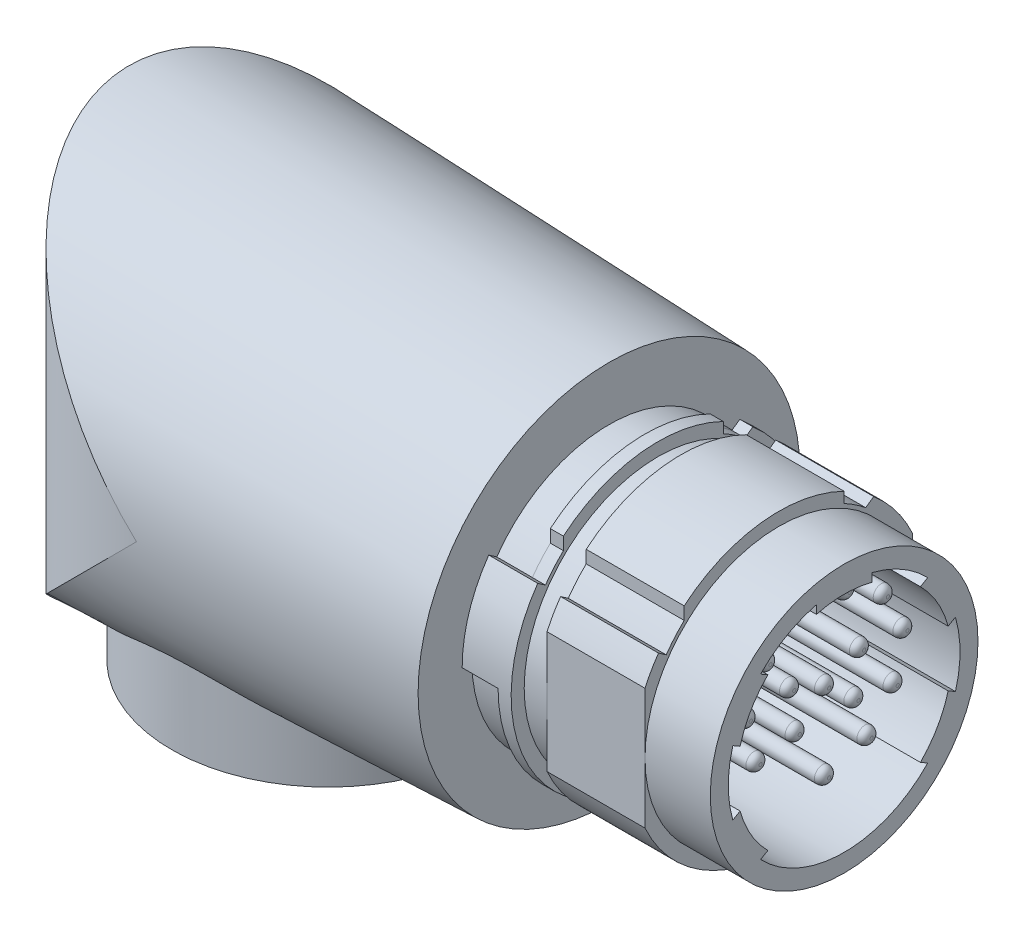
SolidWorks part; units mm, degrees
material "ABS"
ref_plane "Front Plane" through (0, 0, 0) normal (0, 0, 1) x (1, 0, 0)
ref_plane "Top Plane" through (0, 0, 0) normal (0, 1, 0) x (1, 0, 0)
ref_plane "Right Plane" through (0, 0, 0) normal (1, 0, 0) x (0, 0, -1)
sketch "Sketch3" plane through (0, 0, 0) normal (0, 0, 1) x (1, 0, 0)
  line L0 (-15.494, 16.0655) -> (40.132, 16.0655) construction
  line L4 (-15.494, 16.0655) -> (-15.494, 32.258)
  line L5 (-15.494, 32.258) -> (21.844, 30.9245)
  line L6 (21.844, 30.9245) -> (21.844, 28.7655)
  line L7 (21.844, 28.7655) -> (40.132, 28.7655)
  line L8 (40.132, 28.7655) -> (40.132, 16.0655)
  line L9 (40.132, 16.0655) -> (-15.494, 16.0655)
  line L11 (55, 0) -> (-55, 0) construction
  line L12 (0, -55) -> (0, 55) construction
  dimension "D1" = 16.0655
  dimension "D2" = 32.385
  dimension "D3" = 29.718
  dimension "D4" = 25.4
  dimension "D5" = 15.494
  dimension "D6" = 18.288
  dimension "D7" = 55.626
revolve "Revolve1" add sketch "Sketch3" angle 360 about L0
sketch "Sketch4" plane through (0, 0, 0) normal (0, 1, 0) x (1, 0, 0)
  line L0 (21.844, 14.859) -> (-15.494, 16.1925) construction
  line L2 (-15.494, 16.1925) -> (-15.494, -16.1925) construction
  line L3 (-15.494, -16.1925) -> (21.844, -14.859) construction
  line L5 (0.6882, 15.6146) -> (0.6882, 19.05)
  line L6 (0.6882, 19.05) -> (-24.7118, 19.05)
  line L7 (-24.7118, 19.05) -> (-24.7118, -19.05)
  line L8 (-24.7118, -19.05) -> (0.6882, -19.05)
  line L9 (0.6882, -19.05) -> (0.6882, -15.6146)
  line L10 (21.844, 14.859) -> (-15.494, 16.1925) construction
  line L12 (-15.494, -16.1925) -> (21.844, -14.859) construction
  line L14 (0.1305, 0) -> (-15.494, 0) construction
  arc A0 (0.6882, 15.6146) -> (0.6882, -15.6146) centre (0.1305, 0) ccw
  dimension "D1" = 38.1
  dimension "D2" = 25.4
extrude "Extrude3" cut sketch "Sketch4" along normal mid plane 84.582
sketch "Sketch2" plane through (0, 0, 0) normal (0, 1, 0) x (1, 0, 0)
  circle A0 centre (0, 0) radius 12.192
  dimension "D1" = 24.384
extrude "Extrude2" add sketch "Sketch2" along normal blind 7.62
sketch "Sketch5" plane through (0, 0, 0) normal (0, 0, 1) x (1, 0, 0)
  line L0 (21.844, 26.7335) -> (24.638, 26.7335)
  line L1 (21.844, 1.2065) -> (21.844, 30.9245) construction
  line L2 (24.638, 26.7335) -> (24.638, 27.4955)
  line L3 (24.638, 27.4955) -> (25.654, 27.4955)
  line L4 (27.432, 26.4795) -> (27.432, 27.4955)
  line L5 (27.432, 27.4955) -> (35.052, 27.4955)
  line L6 (35.052, 27.4955) -> (35.052, 26.4795)
  line L7 (35.052, 26.4795) -> (40.132, 26.4795)
  line L8 (40.132, 3.3655) -> (40.132, 28.7655) construction
  line L9 (40.132, 26.4795) -> (40.132, 28.7655)
  line L10 (40.132, 28.7655) -> (21.844, 28.7655)
  line L11 (21.844, 28.7655) -> (21.844, 26.7335)
  line L12 (0.6882, 16.0655) -> (40.132, 16.0655) construction
  line L13 (40.132, 16.0655) -> (21.844, 16.0655) construction
  line L14 (-12.1806, 16.0655) -> (21.844, 16.0655) construction
  line L15 (25.654, 27.4955) -> (25.654, 26.4795)
  line L16 (25.654, 26.4795) -> (27.432, 26.4795)
  dimension "D1" = 20.828
  dimension "D2" = 22.86
  dimension "D3" = 20.828
  dimension "D4" = 22.86
  dimension "D5" = 21.336
  dimension "D6" = 5.08
  dimension "D7" = 12.7
  dimension "D8" = 1.778
  dimension "D9" = 15.494
revolve "Cut-Revolve1" cut sketch "Sketch5" angle 360 about L12
sketch "Sketch6" plane through (40.132, 0, 0) normal (1, 0, 0) x (0, 0, -1)
  line L0 (-7.366, 24.8055) -> (-7.366, 23.8226)
  line L1 (-8.7626, 22.2012) -> (-9.3629, 22.6215)
  line L2 (0, 17.8117) -> (0, -17.8117) construction
  line L3 (6.7564, 24.359) -> (7.3787, 24.7947)
  line L4 (5.08, 26.3046) -> (5.08, 25.4795)
  line L5 (0.254, 5.3713) -> (0.254, 4.6383)
  line L6 (3.8593, 6.0887) -> (4.572, 5.5897)
  circle A0 centre (0, 16.0655) radius 11.43 construction
  arc A1 (4.572, 5.5897) -> (0.254, 4.6383) centre (0, 16.0655) cw
  arc A2 (-7.366, 23.8226) -> (-8.7626, 22.2012) centre (0, 16.0655) ccw
  arc A3 (6.7564, 24.359) -> (5.08, 25.4795) centre (0, 16.0655) ccw
  arc A4 (7.3787, 24.7947) -> (5.08, 26.3046) centre (0, 16.0655) ccw
  arc A5 (-7.366, 24.8055) -> (-9.3629, 22.6215) centre (0, 16.0655) ccw
  arc A6 (3.8593, 6.0887) -> (0.254, 5.3713) centre (0, 16.0655) cw
  dimension "D1" = 10.6972
  dimension "D6" = 55
  dimension "D2" = 55
  dimension "D3" = 7.366
  dimension "D4" = 5.08
  dimension "D5" = 1.6764
  dimension "D7" = 0.254
  dimension "D8" = 4.572
  dimension "D9" = 55
extrude "Extrude4" cut sketch "Sketch6" against normal up to surface (18.288 mm away)
sketch "Sketch7" plane through (40.132, 0, 0) normal (1, 0, 0) x (0, 0, -1)
  circle A0 centre (0, 16.0655) radius 9.017
  dimension "D1" = 18.034
extrude "Extrude5" cut sketch "Sketch7" against normal blind 13.97
sketch "Sketch8" plane through (21.844, 0, 0) normal (1, 0, 0) x (0, 0, -1)
  line L0 (-9.3629, 22.6215) -> (-8.7626, 22.2012) construction
  line L1 (-9.3629, 22.6215) -> (-8.7626, 22.2012)
  line L2 (4.572, 5.5897) -> (3.8593, 6.0887) construction
  line L3 (4.572, 5.5897) -> (3.8305, 6.1089)
  line L4 (-8.7626, 22.2012) -> (-8.7387, 22.1844)
  line L5 (-10.668, 16.0655) -> (-11.43, 16.0655)
  line L6 (8.7387, 9.9466) -> (9.3629, 9.5095)
  arc A0 (4.572, 5.5897) -> (7.3787, 24.7947) centre (0, 16.0655) ccw construction
  arc A1 (4.572, 5.5897) -> (9.3629, 9.5095) centre (0, 16.0655) ccw
  circle A2 centre (0, 16.0655) radius 10.668 construction
  arc A3 (-8.7387, 22.1844) -> (-10.668, 16.0655) centre (0, 16.0655) ccw
  arc A4 (-9.3629, 22.6215) -> (0.254, 4.6383) centre (0, 16.0655) ccw construction
  arc A5 (-9.3629, 22.6215) -> (-11.43, 16.0655) centre (0, 16.0655) ccw
  arc A6 (3.8305, 6.1089) -> (8.7387, 9.9466) centre (0, 16.0655) ccw
extrude "Extrude6" add sketch "Sketch8" along normal up to surface (2.794 mm away) up to face at (24.638, 17.8433, 0.0017)
sketch "Sketch9" plane through (40.132, 0, 0) normal (1, 0, 0) x (0, 0, -1)
  line L0 (-9.017, 16.0655) -> (9.017, 16.0655) construction
  line L1 (-15.494, 22.4155) -> (-10.414, 22.4155)
  line L2 (-15.494, 22.4155) -> (-15.494, 9.7155)
  line L3 (-15.494, 9.7155) -> (-10.414, 9.7155)
  line L4 (-10.414, 22.4155) -> (-10.414, 9.7155)
  line L5 (15.494, 22.4155) -> (10.414, 22.4155)
  line L6 (15.494, 22.4155) -> (15.494, 9.7155)
  line L7 (15.494, 9.7155) -> (10.414, 9.7155)
  line L8 (10.414, 22.4155) -> (10.414, 9.7155)
  circle A0 centre (0, 16.0655) radius 10.414 construction
  circle A1 centre (0, 16.0655) radius 9.017 construction
  circle A2 centre (0, 16.0655) radius 9.017 construction
  dimension "D1" = 12.7
  dimension "D2" = 5.08
extrude "Extrude7" cut sketch "Sketch9" against normal up to surface (12.7 mm away) up to face at (27.432, 17.8433, 0.0017)
sketch "Sketch10" plane through (40.132, 0, 0) normal (1, 0, 0) x (0, 0, -1)
  line L0 (-2.159, 24.8202) -> (-2.159, 24.1647)
  line L1 (2.159, 24.1647) -> (2.159, 24.8202)
  line L2 (0, 32.258) -> (0, 16.0655) construction
  line L3 (0, 17.8117) -> (0, -17.8117) construction
  circle A0 centre (0, 16.0655) radius 9.017 construction
  arc A1 (2.159, 24.8202) -> (-2.159, 24.8202) centre (0, 16.0655) ccw
  arc A2 (2.159, 24.1647) -> (-2.159, 24.1647) centre (0, 16.0655) ccw
  spline S0 degree 3 poles (-15.6146, 16.0655) (-15.6186, 16.1773) (-15.6214, 16.2919) (-15.6246, 16.5181) (-15.6256, 16.8571) (-15.6157, 17.1949) (-15.5813, 17.8692) (-15.5391, 18.3167) (-15.3547, 19.6532) (-15.1551, 20.5364) (-14.7333, 21.8486) (-14.5721, 22.2839) (-14.2058, 23.15) (-14.0001, 23.5816) (-13.3217, 24.8493) (-12.7865, 25.6647) (-11.8407, 26.8366) (-11.5015, 27.2186) (-10.769, 27.9633) (-10.3761, 28.3251) (-9.132, 29.3552) (-8.2104, 29.977) (-6.6493, 30.7837) (-6.1065, 31.0271) (-4.9828, 31.4539) (-4.4004, 31.6381) (-3.4923, 31.8657) (-3.1824, 31.9335) (-2.5608, 32.0498) (-2.2486, 32.0985) (-1.3078, 32.216) (-0.6751, 32.2565) (0.6017, 32.2595) (1.2515, 32.2208) (2.5144, 32.0673) (3.1321, 31.9533) (4.3416, 31.6552) (4.9365, 31.4695) (6.0687, 31.0432) (6.61, 30.802) (7.6479, 30.2695) (8.1468, 29.9763) (9.0824, 29.3576) (9.5216, 29.0311) (10.35, 28.3481) (10.7391, 27.9916) (11.4715, 27.2511) (11.8162, 26.8652) (12.7723, 25.6857) (13.308, 24.8707) (14.2101, 23.1931) (14.5761, 22.3304) (15.1496, 20.5604) (15.352, 19.6686) (15.5385, 18.3235) (15.581, 17.8737) (15.6156, 17.1971) (15.6223, 16.9712) (15.6249, 16.6318) (15.6246, 16.5186) (15.6214, 16.2921) (15.6186, 16.1773) (15.6146, 16.0655) knots 0 0 0 0 0.007812 0.007812 0.015625 0.03125 0.03125 0.0625 0.0625 0.125 0.125 0.15625 0.15625 0.1875 0.1875 0.25 0.25 0.28125 0.28125 0.3125 0.3125 0.375 0.375 0.40625 0.40625 0.4375 0.4375 0.453125 0.453125 0.46875 0.46875 0.5 0.5 0.53125 0.53125 0.5625 0.5625 0.59375 0.59375 0.625 0.625 0.65625 0.65625 0.6875 0.6875 0.71875 0.71875 0.75 0.75 0.8125 0.8125 0.875 0.875 0.9375 0.9375 0.96875 0.96875 0.984375 0.984375 0.992188 0.992188 1 1 1 1 construction
  dimension "D1" = 16.764
  dimension "D2" = 4.318
extrude "Extrude8" add sketch "Sketch10" against normal up to surface (13.97 mm away) up to face at (26.162, 16.0655, -9.017)
pattern_circular "CirPattern1" count 6 over 360 about axis through (0, 16.0655, 0) along (1, 0, 0) skipping 3 of "Extrude8"
sketch "Sketch11" plane through (26.162, 0, 0) normal (1, 0, 0) x (0, 0, -1)
  line L0 (0, 24.4475) -> (0, 17.3926) construction
  line L1 (0, 17.8117) -> (0, -17.8117) construction
  circle A0 centre (-2.7178, 18.7325) radius 0.635
  circle A1 centre (2.7178, 18.7325) radius 0.635
  circle A2 centre (-2.286, 15.5575) radius 0.635
  circle A3 centre (2.286, 15.5575) radius 0.635
  arc A4 (2.159, 24.1647) -> (-2.159, 24.1647) centre (0, 16.0655) ccw construction
  circle A5 centre (0, 17.5387) radius 0.635
  dimension "D3" = 1.27
  dimension "D1" = 2.667
  dimension "D2" = 5.4356
  dimension "D4" = 4.572
  dimension "D5" = 0.508
  dimension "D6" = 1.4732
extrude "Extrude9" add sketch "Sketch11" along normal blind 12.8016
sketch "Sketch12" plane through (26.162, 0, 0) normal (1, 0, 0) x (0, 0, -1)
  line L0 (0, 17.8117) -> (0, -17.8117) construction
  line L1 (0, 24.4475) -> (0, 5.6515) construction
  circle A0 centre (-6.096, 18.3515) radius 0.635
  circle A1 centre (6.096, 18.3515) radius 0.635
  circle A2 centre (4.572, 21.3995) radius 0.635
  circle A3 centre (3.302, 12.5095) radius 0.635
  circle A4 centre (0, 11.4935) radius 0.635
  circle A5 centre (-4.572, 21.3995) radius 0.635
  circle A6 centre (1.6002, 23.1775) radius 0.635
  circle A7 centre (5.334, 15.0495) radius 0.635
  circle A9 centre (-5.334, 15.0495) radius 0.635
  arc A10 (2.159, 24.1647) -> (-2.159, 24.1647) centre (0, 16.0655) ccw construction
  circle A11 centre (0, 16.0655) radius 10.414 construction
  dimension "D1" = 1.016
  dimension "D2" = 1.27
  dimension "D3" = 4.572
  dimension "D4" = 3.302
  dimension "D5" = 10.668
  dimension "D6" = 3.556
  dimension "D7" = 12.192
  dimension "D8" = 9.144
  dimension "D9" = 2.286
  dimension "D10" = 5.334
  dimension "D11" = 1.6002
  dimension "D12" = 7.112
extrude "Extrude10" add sketch "Sketch12" along normal up to surface (12.8016 mm away) up to face at (38.9636, 18.7325, -3.3528)
fillet "Fillet1" radius 0.508 14 edges at (38.9636, 15.5575, 1.651) (38.9636, 18.7325, 2.0828) (38.9636, 15.5575, -2.921) (38.9636, 18.7325, -3.3528) (38.9636, 21.3995, 3.937) (38.9636, 12.5095, -3.937) (38.9636, 17.5387, -0.635) (38.9636, 21.3995, -5.207) (38.9636, 23.1775, -2.2352) (38.9636, 18.3515, 5.461) (38.9636, 15.0495, 4.699) (38.9636, 11.4935, -0.635) (38.9636, 15.0495, -5.969) (38.9636, 18.3515, -6.731)
